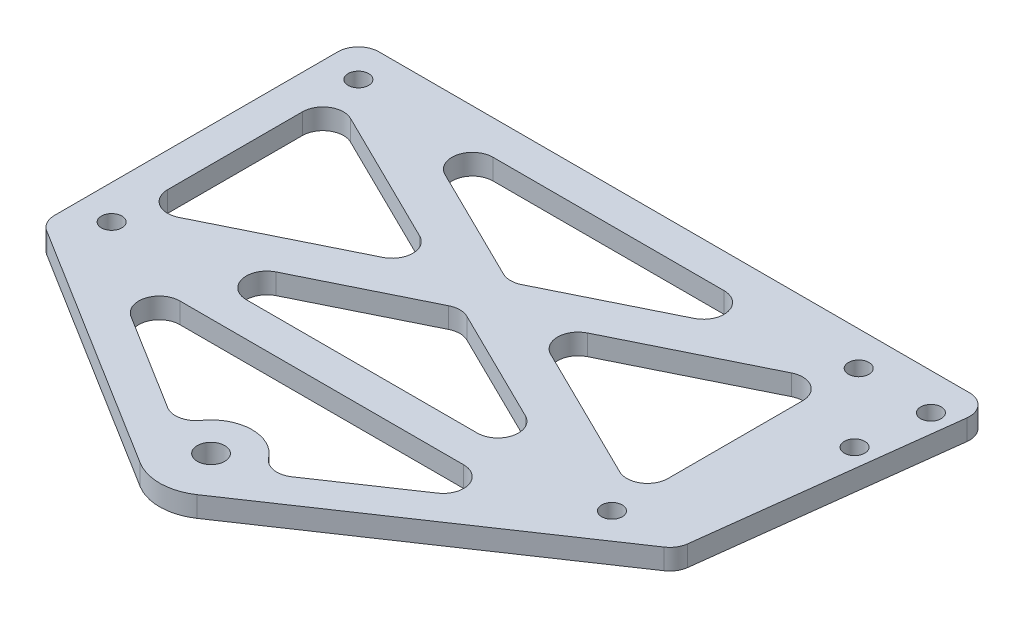
SolidWorks part; units mm, degrees
material "Thornel Mat VMA"
ref_plane "前视基准面" through (0, 0, 0) normal (0, 0, 1) x (1, 0, 0)
ref_plane "上视基准面" through (0, 0, 0) normal (0, 1, 0) x (1, 0, 0)
ref_plane "右视基准面" through (0, 0, 0) normal (1, 0, 0) x (0, 0, -1)
other "Configuration Table"
sketch "草图1" plane through (0, 0, 0) normal (0, 1, 0) x (1, 0, 0)
  line L1 (36.5, -18) -> (-36.5, -18) construction
  line L2 (36.5, -18) -> (36.5, 18) construction
  line L3 (36.5, 18) -> (-36.5, 18) construction
  line L4 (-36.5, -18) -> (-36.5, 18) construction
  line L5 (36.5, -18) -> (-36.5, 18) construction
  line L6 (36.5, 18) -> (-36.5, -18) construction
  line L11 (51.0583, 23) -> (-41.5, 23)
  line L13 (-41.5, 23) -> (-41.5, -23)
  line L19 (-3.9636, -46.3671) -> (-41.5, -23)
  line L21 (46.0242, -18) -> (4.1942, -46.2176)
  line L22 (47.3796, 17.6556) -> (46.1609, 7.7302) construction
  line L23 (0, 0) -> (0, 11.838) construction
  line L24 (0, 0) -> (-10.2724, 0) construction
  line L25 (-29.7172, 18) -> (29.7172, 18)
  line L26 (29.7172, 18) -> (0, 3.345)
  line L27 (0, 3.345) -> (-29.7172, 18)
  line L28 (-36.5, 14.655) -> (-36.5, -14.655)
  line L29 (-36.5, -14.655) -> (-6.7828, 0)
  line L30 (-6.7828, 0) -> (-36.5, 14.655)
  line L33 (46.1609, 7.7302) -> (39.7018, -44.8748) construction
  line L34 (29.7172, -18) -> (0, -3.345)
  line L35 (-29.7172, -18) -> (29.7172, -18)
  line L36 (0, -3.345) -> (-29.7172, -18)
  line L37 (36.5, -14.655) -> (6.7828, 0)
  line L38 (36.5, 14.655) -> (36.5, -14.655)
  line L39 (6.7828, 0) -> (36.5, 14.655)
  line L43 (46.0242, -18) -> (51.0583, 23)
  line L45 (0, -40) -> (39.7018, -44.8748) construction
  line L46 (-32.039, -23) -> (29.6713, -23)
  line L47 (29.6713, -23) -> (5.9198, -39.0223)
  line L48 (-32.039, -23) -> (-5.9516, -39.2398)
  circle A0 centre (-36.5, 18) radius 1.5
  circle A1 centre (36.5, 18) radius 1.5
  circle A2 centre (36.5, -18) radius 1.5
  circle A3 centre (-36.5, -18) radius 1.5
  circle A4 centre (0, -40) radius 2
  arc A10 (-3.9636, -46.3671) -> (4.1942, -46.2176) centre (0, -40) ccw
  circle A11 centre (46.1609, 7.7302) radius 1.5
  circle A12 centre (47.3796, 17.6556) radius 1.5
  arc A13 (5.9198, -39.0223) -> (-5.9516, -39.2398) centre (0, -40) ccw
  point P0 (0, 0)
  point P10 (0, 0)
  point P15 (0, -40)
  dimension "D3" = 3
  dimension "D8" = 4
  dimension "D7" = 7.5
  dimension "D10" = 5
  dimension "D4" = 5
  dimension "D11" = 7
  dimension "D12" = 10
  dimension "D14" = 3
  dimension "D16" = 12
  dimension "D18" = 5
  dimension "D13" = 3
  dimension "D1" = 73
  dimension "D2" = 36
  dimension "D5" = 5
  dimension "D6" = 43
  dimension "D9" = 22
  dimension "D15" = 53
  dimension "D17" = 3
  dimension "D19" = 5
  dimension "D20" = 5
extrude "凸台-拉伸1" add sketch "草图1" along normal blind 3
fillet "圆角1" radius 3 20 edges at (6.7828, 1.5, 0) (36.5, 1.5, 14.655) (36.5, 1.5, -14.655) (0, 1.5, 3.345) (-29.7172, 1.5, 18) (29.7172, 1.5, 18) (-36.5, 1.5, 14.655) (-6.7828, 1.5, 0) (-36.5, 1.5, -14.655) (29.7172, 1.5, -18) (-29.7172, 1.5, -18) (0, 1.5, -3.345) (-41.5, 1.5, 23) (51.0583, 1.5, -23) (-41.5, 1.5, -23) (46.0242, 1.5, 18) (5.9198, 1.5, 39.0223) (29.6713, 1.5, 23) (-32.039, 1.5, 23) (-5.9516, 1.5, 39.2398)
